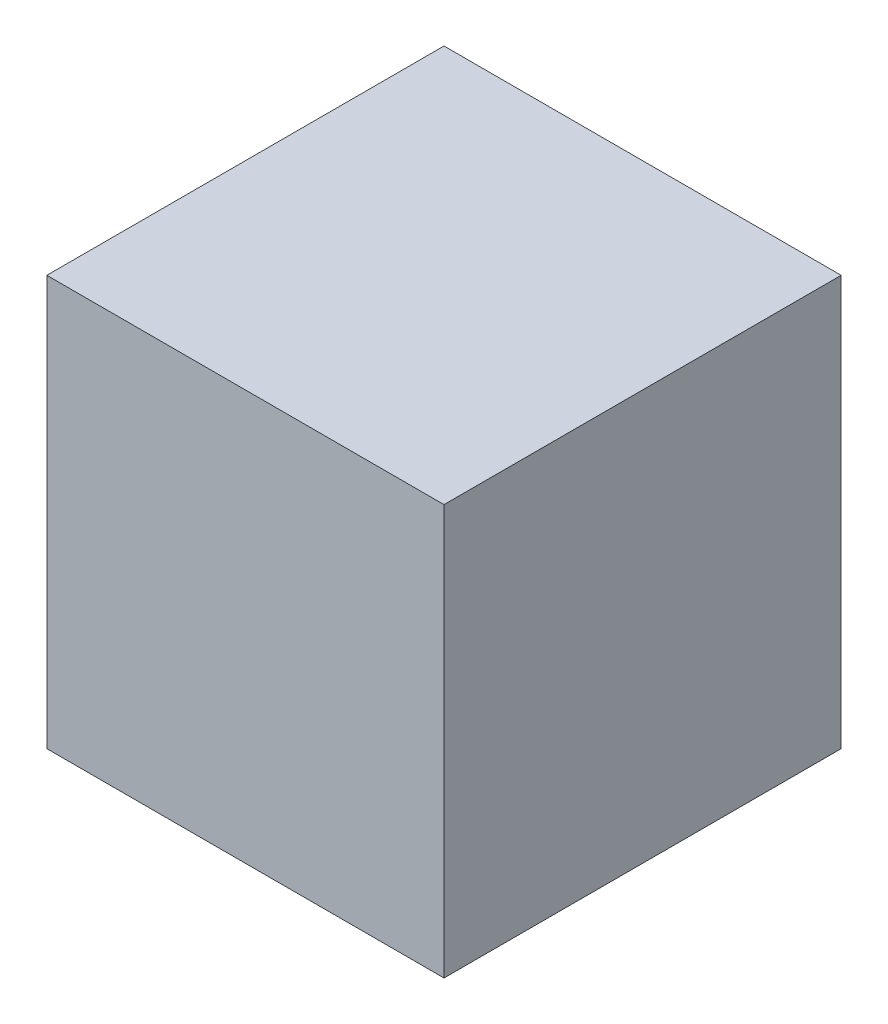
SolidWorks part; units mm, degrees
ref_plane "Front Plane" through (0, 0, 0) normal (0, 0, 1) x (1, 0, 0)
ref_plane "Top Plane" through (0, 0, 0) normal (0, 1, 0) x (1, 0, 0)
ref_plane "Right Plane" through (0, 0, 0) normal (1, 0, 0) x (0, 0, -1)
sketch "Sketch1" plane through (0, 0, 0) normal (0, 1, 0) x (1, 0, 0)
  line L1 (-15.5, 15.5) -> (15.5, 15.5)
  line L2 (-15.5, 15.5) -> (-15.5, -15.5)
  line L3 (-15.5, -15.5) -> (15.5, -15.5)
  line L4 (15.5, 15.5) -> (15.5, -15.5)
  line L5 (-15.5, 15.5) -> (15.5, -15.5) construction
  line L6 (-15.5, -15.5) -> (15.5, 15.5) construction
  point P0 (0, 0)
  dimension "D1" = 31
  dimension "D2" = 31
extrude "Boss-Extrude1" add sketch "Sketch1" along normal blind 32
